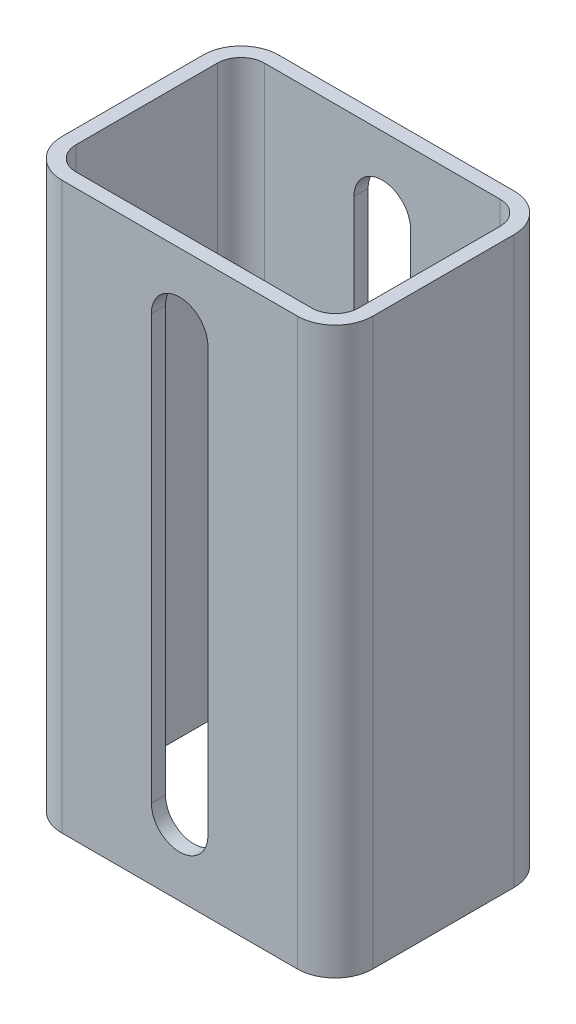
SolidWorks part; units mm, degrees
ref_plane "Front Plane" through (0, 0, 0) normal (0, 0, 1) x (1, 0, 0)
ref_plane "Top Plane" through (0, 0, 0) normal (0, 1, 0) x (1, 0, 0)
ref_plane "Right Plane" through (0, 0, 0) normal (1, 0, 0) x (0, 0, -1)
sketch "Sketch1" plane through (0, 0, 0) normal (0, 1, 0) x (1, 0, 0)
  line L1 (-25, -20) -> (25, -20)
  line L2 (-30, -15) -> (-30, 15)
  line L3 (-25, 20) -> (25, 20)
  line L4 (30, -15) -> (30, 15)
  line L5 (-30, -20) -> (30, 20) construction
  line L6 (-30, 20) -> (30, -20) construction
  arc A0 (25, -20) -> (30, -15) centre (25, -15) ccw
  arc A1 (-25, -20) -> (-30, -15) centre (-25, -15) cw
  arc A2 (-30, 15) -> (-25, 20) centre (-25, 15) cw
  arc A3 (25, 20) -> (30, 15) centre (25, 15) cw
  point P0 (0, 0)
  dimension "D3" = 5
  dimension "width" = 60
  dimension "width2" = 40
extrude "Extrude-Thin1" add sketch "Sketch1" along normal mid plane 120 thin
sketch "Sketch2" plane through (0, 0, 23) normal (0, 0, 1) x (1, 0, 0)
  line L0 (0, 45) -> (0, -45) construction
  line L1 (6, 45) -> (6, -45)
  line L2 (-6, 45) -> (-6, -45)
  line L3 (-25, 0) -> (25, 0) construction
  line L4 (-25, 60) -> (-25, -60) construction
  line L5 (25, 60) -> (25, -60) construction
  arc A0 (6, 45) -> (-6, 45) centre (0, 45) ccw
  arc A1 (-6, -45) -> (6, -45) centre (0, -45) ccw
  point P3 (0, 0)
  dimension "D1" = 6
  dimension "D2" = 90
extrude "Cut-Extrude1" cut sketch "Sketch2" against normal through all both and the other way through all
